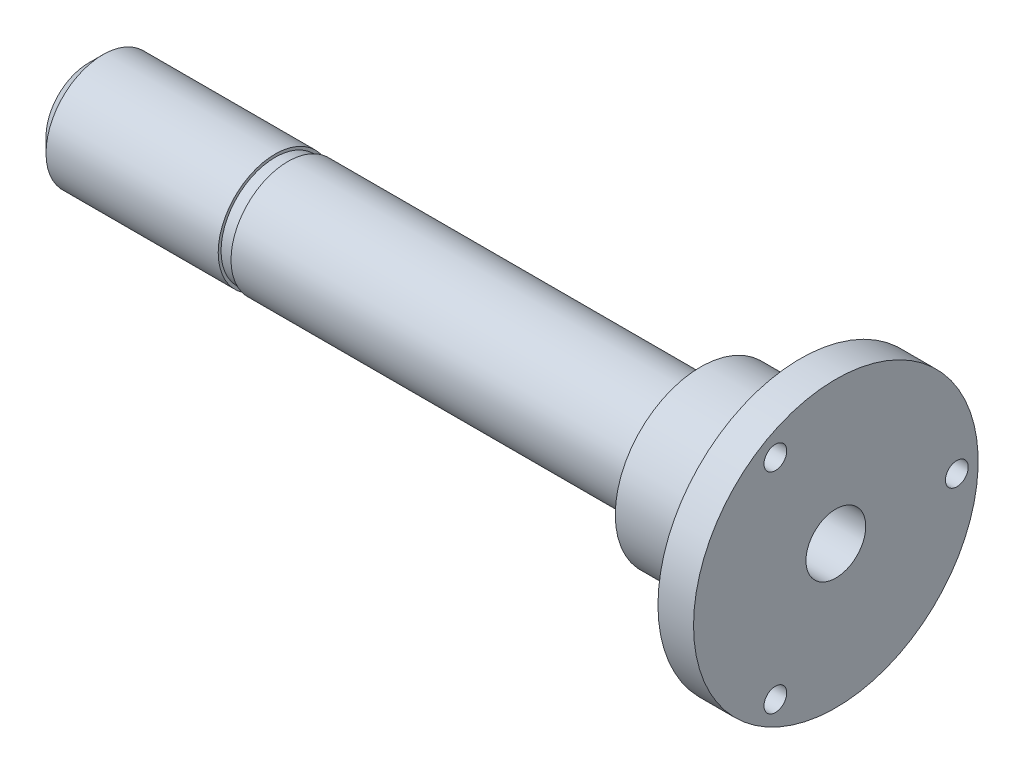
SolidWorks part; units mm, degrees
material "201 Annealed Stainless Steel (SS)"
ref_plane "Front Plane" through (0, 0, 0) normal (0, 0, 1) x (1, 0, 0)
ref_plane "Top Plane" through (0, 0, 0) normal (0, 1, 0) x (1, 0, 0)
ref_plane "Right Plane" through (0, 0, 0) normal (1, 0, 0) x (0, 0, -1)
ref_plane "Plane1" through (0, 0, 0) normal (0, 0, -1) x (-1, 0, 0)
sketch "Sketch1" plane through (0, 0, 0) normal (0, 0, -1) x (-1, 0, 0)
  line L1 (13.2124, 0) -> (50, 0) construction
  line L2 (50, 2.1) -> (50, 3)
  line L3 (49, 4) -> (36.9, 4)
  line L4 (36.9, 4) -> (36.9, 3.8)
  line L5 (36.9, 3.8) -> (36, 3.8)
  line L6 (36, 3.8) -> (36, 4)
  line L7 (36, 4) -> (7.2, 4)
  line L8 (7, 4.2) -> (7, 6)
  line L9 (7, 6) -> (0, 6)
  line L10 (0, 6) -> (0, 10)
  line L11 (0, 10) -> (-2.5, 10)
  line L12 (-2.5, 10) -> (-2.5, 2.1)
  line L13 (-2.5, 2.1) -> (50, 2.1)
  line L14 (0, 0) -> (50, 0) construction
  arc A0 (7.2, 4) -> (7, 4.2) centre (7.2, 4.2) cw
  spline S0 degree 3 poles (49, 4) (49.3333, 3.6667) (49.6667, 3.3333) (50, 3) knots 0 0 0 0 1 1 1 1
  dimension "D1" = 4
  dimension "D2" = 6
  dimension "D3" = 10
  dimension "D4" = 2.1
  dimension "D5" = 2.5
  dimension "D6" = 7
revolve "Revolve1" add sketch "Sketch1" angle 360 about L14
hole_wizard "M2x0.4 Tapped Hole1" positions "Sketch5" profile "Sketch4" tap size "M2x0.4" standard "ANSI Metric" end condition up to next
sketch "Sketch5" plane through (2.5, 0, 0) normal (1, 0, 0) x (0, 0, -1)
  line L5 (0, 0) -> (10, 0) construction
  line L6 (0, 0) -> (-4.25, 7.3612) construction
  circle A1 centre (0, 0) radius 10 construction
  circle A3 centre (0, 0) radius 8.5 construction
  point P0 (8.5, 0)
  point P3 (-4.25, 7.3612)
  point P69 (-4.25, -7.3612)
  dimension "D3" = 17
  dimension "D1" = 120
cosmetic thread "Hole Thread1" parameters "D2"=2
sketch "Sketch4" plane through (2.5, 0, -8.5) normal (0, 1, 0) x (0, 0, -1)
  line L0 (0, 0) -> (0, 2.5)
  line L1 (0, 2.5) -> (0.8, 2.5)
  line L2 (0.8, 2.5) -> (0.8, 0)
  line L5 (0.8, 0) -> (0, 0)
  line L11 (0, -6.35) -> (0, 107.95) construction
  dimension "Thru Tap Drill Dia." = 1.6
  dimension "Thru Tap Drill Depth" = 2.5
cosmetic thread "Hole Thread2" parameters "D2"=2
cosmetic thread "Hole Thread3" parameters "D2"=2
